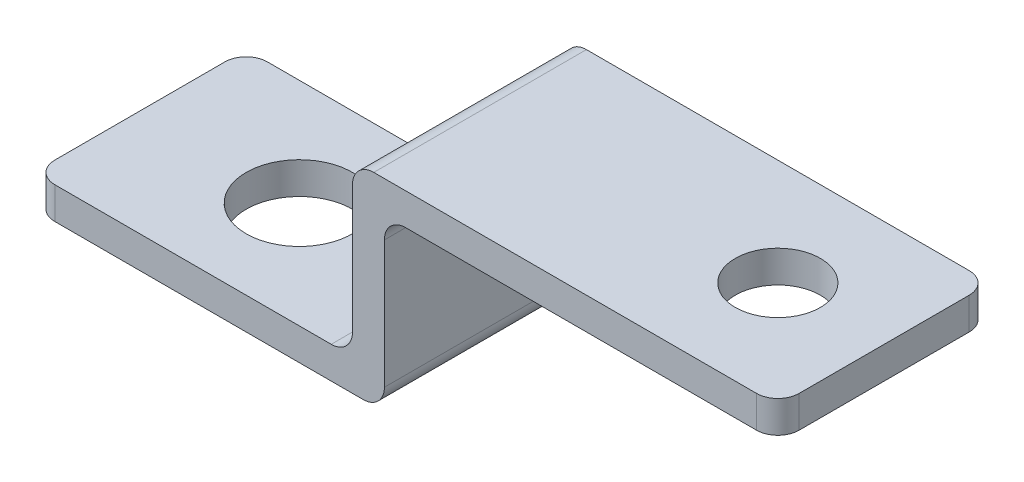
SolidWorks part; units mm, degrees
ref_plane "Ön Düzlem" through (0, 0, 0) normal (0, 0, 1) x (1, 0, 0)
ref_plane "Üst Düzlem" through (0, 0, 0) normal (0, 1, 0) x (1, 0, 0)
ref_plane "Sağ Düzlem" through (0, 0, 0) normal (1, 0, 0) x (0, 0, -1)
sketch "Sketch1" plane through (0, 0, 0) normal (0, 0, 1) x (1, 0, 0)
  line L0 (0, 0) -> (15, 0)
  line L1 (15, 0) -> (15, 8)
  line L2 (15, 8) -> (35, 8)
extrude "Extrude-Thin1" add sketch "Sketch1" along normal blind 10 thin
sketch "Sketch2" plane through (0, 8, 0) normal (0, 1, 0) x (1, 0, 0)
  line L0 (0, -10) -> (0, 0) construction
  line L1 (35, -10) -> (35, 0) construction
  line L2 (0, 0) -> (15, 0) construction
  line L3 (15, -10) -> (35, -10) construction
  circle A0 centre (30, -5) radius 2
  circle A1 centre (7.5, -5) radius 2.5
  point P6 (0, -5)
  dimension "D1" = 7.5
  dimension "D2" = 5
  dimension "D3" = 5
  dimension "D4" = 5
extrude "Cut-Extrude1" cut sketch "Sketch2" against normal through all
fillet "Fillet2" radius 1 8 edges at (15, 0, 5) (16.5, 6.5, 5) (15, 8, 5) (16.5, -1.5, 5) (35, 7.25, 10) (35, 7.25, 0) (0, -0.75, 10) (0, -0.75, 0)
